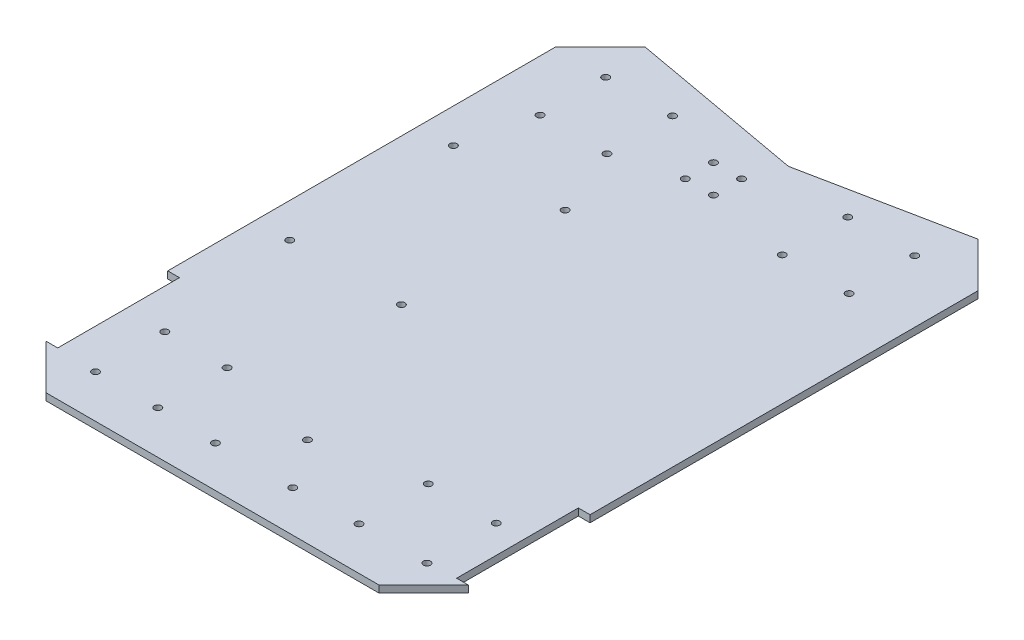
SolidWorks part; units mm, degrees
ref_plane "前视基准面" through (0, 0, 0) normal (0, 0, 1) x (1, 0, 0)
ref_plane "上视基准面" through (0, 0, 0) normal (0, 1, 0) x (1, 0, 0)
ref_plane "右视基准面" through (0, 0, 0) normal (1, 0, 0) x (0, 0, -1)
sketch "草图2" plane through (0, 0, 0) normal (0, 1, 0) x (1, 0, 0)
  line L1 (-276.0634, 188.4918) -> (-95.9897, 188.4918)
  line L2 (-276.0634, 188.4918) -> (-276.0634, -66.9188)
  line L3 (-276.0634, -66.9188) -> (-95.9897, -66.9188)
  line L4 (-95.9897, 188.4918) -> (-95.9897, -66.9188)
extrude "凸台-拉伸1" add sketch "草图2" along normal blind 3
sketch "草图4" plane through (0, 3, 0) normal (0, 1, 0) x (1, 0, 0)
  line L0 (-95.9897, -47.8767) -> (-115.0318, -66.9188)
  line L1 (-95.9897, -66.9188) -> (-95.9897, 188.4918) construction
  line L2 (-276.0634, -66.9188) -> (-95.9897, -66.9188) construction
  line L3 (-276.0634, -47.8767) -> (-257.0213, -66.9188)
  line L4 (-276.0634, 188.4918) -> (-276.0634, -66.9188) construction
  line L5 (-115.0318, 188.4918) -> (-101.5072, 174.9672)
  line L6 (-95.9897, 188.4918) -> (-276.0634, 188.4918) construction
  line L7 (-101.5072, 174.9672) -> (-95.9897, 169.4497)
  line L8 (-257.0213, 188.4918) -> (-276.0634, 169.4497)
  line L9 (-174.9035, 174.9672) -> (-182.3189, 174.9672)
  line L10 (-182.3189, 174.9672) -> (-115.0318, 188.4918)
  line L11 (-257.0213, 188.4918) -> (-182.3189, 174.9672)
  line M2 (-276.0634, 188.4918) -> (-276.0634, -66.9188)
  line M3 (-276.0634, -66.9188) -> (-95.9897, -66.9188)
  line M4 (-95.9897, -66.9188) -> (-95.9897, 188.4918)
  line M5 (-95.9897, 188.4918) -> (-276.0634, 188.4918)
extrude "切除-拉伸1" cut sketch "草图4" against normal blind 3 contours L8 M5 M2 | L11 L10 M5 | L0 M4 M3 | L5 L7 M4 M5 | L3 M2 M3
sketch "草图5" plane through (0, 3, 0) normal (0, 1, 0) x (1, 0, 0)
  line L0 (-276.0634, 4.0306) -> (-271.0634, 4.0306)
  line L1 (-95.9897, -47.8767) -> (-95.9897, 169.4497) construction
  line L2 (-276.0634, -47.8767) -> (-271.0634, -47.8767)
  line L3 (-276.0634, 169.4497) -> (-276.0634, -47.8767) construction
  line L4 (-257.0213, -66.9188) -> (-115.0318, -66.9188) construction
  line L5 (-271.0634, 4.0306) -> (-271.0634, -47.8767)
  line L6 (-95.9897, -47.8767) -> (-100.9897, -47.8767)
  line L7 (-100.9897, -47.8767) -> (-100.9897, 4.0306)
  line L8 (-100.9897, 4.0306) -> (-95.9897, 4.0306)
  line L15 (-276.0634, 4.0306) -> (-276.0634, -47.8767)
  line L16 (-95.9897, 4.0306) -> (-95.9897, -47.8767)
  dimension "D1" = 180.0737
  dimension "D2" = 255.4107
extrude "切除-拉伸2" cut sketch "草图5" against normal blind 3
sketch "草图7" plane through (0, 3, 0) normal (0, 1, 0) x (1, 0, 0)
  line L1 (-260.4651, -14.1513) -> (-220.4651, -14.1513)
  line L2 (-260.4651, -14.1513) -> (-260.4651, -54.1513)
  line L3 (-260.4651, -54.1513) -> (-220.4651, -54.1513)
  line L4 (-220.4651, -14.1513) -> (-220.4651, -54.1513)
  line L5 (-148.0942, -14.1513) -> (-108.0942, -14.1513)
  line L6 (-148.0942, -14.1513) -> (-148.0942, -54.1513)
  line L7 (-148.0942, -54.1513) -> (-108.0942, -54.1513)
  line L8 (-108.0942, -14.1513) -> (-108.0942, -54.1513)
  line L9 (-260.4651, 176.3659) -> (-220.4651, 176.3659)
  line L10 (-260.4651, 176.3659) -> (-260.4651, 136.3659)
  line L11 (-260.4651, 136.3659) -> (-220.4651, 136.3659)
  line L12 (-220.4651, 176.3659) -> (-220.4651, 136.3659)
  line L13 (-156.6504, 176.3659) -> (-116.6504, 176.3659)
  line L14 (-156.6504, 176.3659) -> (-156.6504, 136.3659)
  line L15 (-156.6504, 136.3659) -> (-116.6504, 136.3659)
  line L16 (-116.6504, 176.3659) -> (-116.6504, 136.3659)
hole_wizard "大小mm Transitional 暗销孔1" positions "草图8" profile "草图9" hole size "Ø3.0" standard "AS" end condition through all
sketch "草图8" plane through (0, 3, 0) normal (0, 1, 0) x (1, 0, 0)
  point P0 (-254.1906, 168.8793)
  point P2 (-254.1906, 140.9292)
  point P4 (-225.6701, 168.8793)
  point P6 (-225.6701, 140.9292)
  point P8 (-150.9463, 168.8793)
  point P10 (-150.9463, 140.9292)
sketch "草图9" plane through (-254.1906, 3, -168.8793) normal (1, 0, 0) x (0, 0, 1)
  line L0 (0, 0) -> (0, 3)
  line L1 (0, 3) -> (1.5, 3)
  line L2 (1.5, 3) -> (1.5, 0)
  line L5 (1.5, 0) -> (0, 0)
  line L11 (0, -6.35) -> (0, 107.95) construction
  dimension "通孔孔直径" = 3
  dimension "通孔孔深度" = 3
hole_wizard "大小mm Transitional 暗销孔2" positions "草图10" profile "草图11" hole size "Ø3.0" standard "AS" end condition through all
sketch "草图10" plane through (0, 3, 0) normal (0, 1, 0) x (1, 0, 0)
  point P0 (-122.4257, 168.8793)
  point P2 (-122.4257, 140.9292)
  point P4 (-254.1906, -19.0806)
  point P6 (-254.1906, -48.6233)
  point P8 (-227.6467, -19.0806)
  point P10 (-227.6467, -48.6233)
  point P12 (-141.8592, -19.0806)
  point P14 (-141.8592, -48.6233)
  point P16 (-112.8846, -19.0806)
  point P18 (-112.8846, -48.6233)
sketch "草图11" plane through (-122.4257, 3, -168.8793) normal (1, 0, 0) x (0, 0, 1)
  line L0 (0, 0) -> (0, 3)
  line L1 (0, 3) -> (1.5, 3)
  line L2 (1.5, 3) -> (1.5, 0)
  line L5 (1.5, 0) -> (0, 0)
  line L11 (0, -6.35) -> (0, 107.95) construction
  dimension "通孔孔直径" = 3
  dimension "通孔孔深度" = 3
sketch "草图12" plane through (0, 3, 0) normal (0, 1, 0) x (1, 0, 0)
  line L1 (-266.596, 33.7816) -> (-208.596, 33.7816)
  line L2 (-266.596, 33.7816) -> (-266.596, 118.7816)
  line L3 (-266.596, 118.7816) -> (-208.596, 118.7816)
  line L4 (-208.596, 33.7816) -> (-208.596, 118.7816)
  line L5 (-266.596, 33.7816) -> (-208.596, 118.7816) construction
  line L6 (-266.596, 118.7816) -> (-208.596, 33.7816) construction
  point P0 (-237.596, 76.2816)
hole_wizard "大小mm 暗销孔1" positions "草图13" profile "草图14" hole size "Ø3.0" standard "IS" end condition through all
sketch "草图13" plane through (0, 3, 0) normal (0, 1, 0) x (1, 0, 0)
  line L0 (-266.596, 118.7816) -> (-208.596, 33.7816) construction
  line L1 (-266.596, 33.7816) -> (-208.596, 118.7816) construction
  point P0 (-261.4118, 111.1839)
  point P4 (-261.4118, 41.3792)
  point P8 (-213.7803, 41.3792)
  point P10 (-213.7803, 111.1839)
sketch "草图14" plane through (-261.4118, 3, -111.1839) normal (1, 0, 0) x (0, 0, 1)
  line L0 (0, 0) -> (0, 3)
  line L1 (0, 3) -> (1.5, 3)
  line L2 (1.5, 3) -> (1.5, 0)
  line L5 (1.5, 0) -> (0, 0)
  line L11 (0, -6.35) -> (0, 107.95) construction
  dimension "通孔孔直径" = 3
  dimension "通孔孔深度" = 3
sketch "草图42" plane through (0, 0, 0) normal (0, -1, 0) x (-1, 0, 0)
  line L1 (154.4872, -9.4462) -> (109.4872, -9.4462)
  line L2 (154.4872, -9.4462) -> (154.4872, 130.5538)
  line L3 (154.4872, 130.5538) -> (109.4872, 130.5538)
  line L4 (109.4872, -9.4462) -> (109.4872, 130.5538)
sketch "草图45" plane through (0, 0, 0) normal (0, -1, 0) x (-1, 0, 0)
  line L1 (235.7851, 50.7533) -> (132.5851, 50.7533)
  line L2 (235.7851, 50.7533) -> (235.7851, 105.9533)
  line L3 (235.7851, 105.9533) -> (132.5851, 105.9533)
  line L4 (132.5851, 50.7533) -> (132.5851, 105.9533)
  circle A0 centre (189.9184, 4.8865) radius 20
sketch "草图49" plane through (0, 0, 0) normal (0, -1, 0) x (1, 0, 0)
  line L1 (-220.0843, 59.2917) -> (-149.5493, 59.2917)
  line L2 (-220.0843, 59.2917) -> (-220.0843, 16.7917)
  line L3 (-220.0843, 16.7917) -> (-149.5493, 16.7917)
  line L4 (-149.5493, 59.2917) -> (-149.5493, 16.7917)
  point P4 (-220.0843, 38.0417)
  dimension "D1" = 21.25
hole_wizard "大小mm 暗销孔2" positions "草图50" profile "草图51" hole size "Ø3.0" standard "BSI" end condition through all
sketch "草图50" plane through (0, 0, 0) normal (0, -1, 0) x (-1, 0, 0)
  point P0 (202.3176, -49.3907)
  point P2 (169.3491, -49.3907)
  point P4 (183.8709, -28.5891)
sketch "草图51" plane through (-202.3176, 0, 49.3907) normal (1, 0, 0) x (0, 0, -1)
  line L0 (0, 0) -> (0, 3)
  line L1 (0, 3) -> (1.5, 3)
  line L2 (1.5, 3) -> (1.5, 0)
  line L5 (1.5, 0) -> (0, 0)
  line L11 (0, -6.35) -> (0, 107.95) construction
  dimension "通孔孔直径" = 3
  dimension "通孔孔深度" = 3
sketch "草图53" plane through (0, 0, 0) normal (0, -1, 0) x (1, 0, 0)
  line L1 (-199.7071, -148.355) -> (-187.7071, -148.355)
  line L2 (-199.7071, -148.355) -> (-199.7071, -160.355)
  line L3 (-199.7071, -160.355) -> (-187.7071, -160.355)
  line L4 (-187.7071, -148.355) -> (-187.7071, -160.355)
hole_wizard "大小mm 暗销孔3" positions "草图54" profile "草图55" hole size "Ø3.0" standard "BSI" end condition through all
sketch "草图54" plane through (0, 0, 0) normal (0, -1, 0) x (-1, 0, 0)
  point P0 (199.7071, 148.355)
  point P3 (187.7071, 148.355)
  point P6 (199.7071, 160.355)
  point P9 (187.7071, 160.355)
sketch "草图55" plane through (-199.7071, 0, -148.355) normal (1, 0, 0) x (0, 0, -1)
  line L0 (0, 0) -> (0, 3)
  line L1 (0, 3) -> (1.5, 3)
  line L2 (1.5, 3) -> (1.5, 0)
  line L5 (1.5, 0) -> (0, 0)
  line L11 (0, -6.35) -> (0, 107.95) construction
  dimension "通孔孔直径" = 3
  dimension "通孔孔深度" = 3
